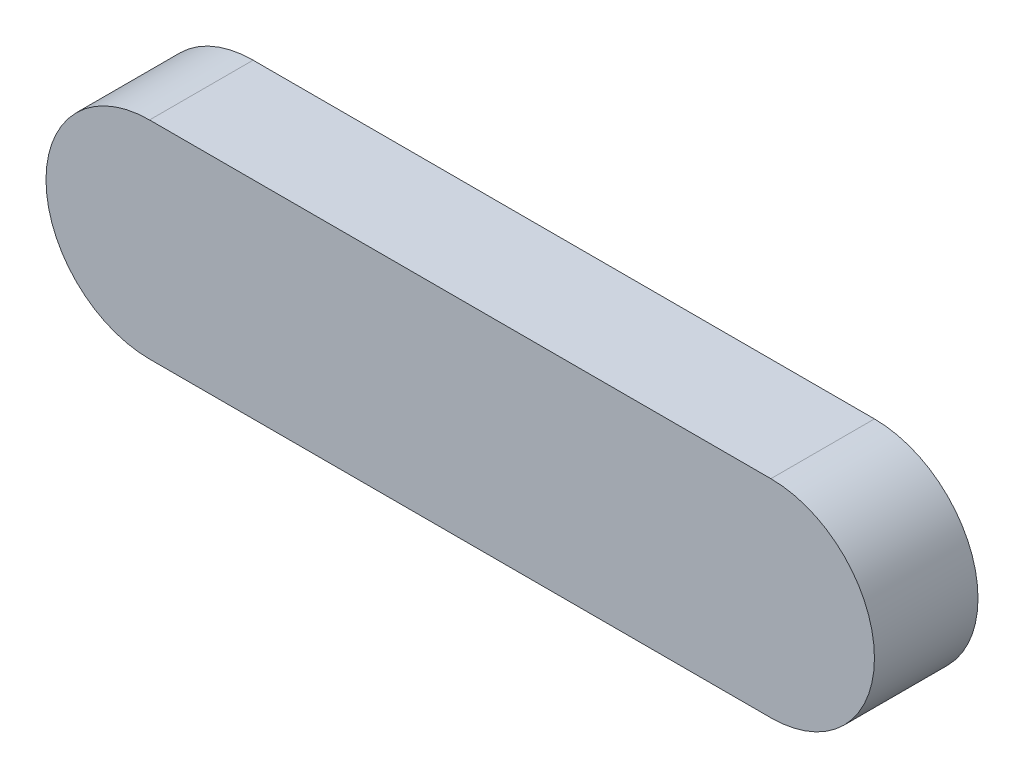
SolidWorks part; units mm, degrees
ref_plane "Front Plane" through (0, 0, 0) normal (0, 0, 1) x (1, 0, 0)
ref_plane "Top Plane" through (0, 0, 0) normal (0, 1, 0) x (1, 0, 0)
ref_plane "Right Plane" through (0, 0, 0) normal (1, 0, 0) x (0, 0, -1)
sketch "Sketch1" plane through (0, 0, 0) normal (0, 0, 1) x (1, 0, 0)
  line L0 (-15, 0) -> (15, 0) construction
  line L1 (-15, 5) -> (15, 5)
  line L2 (-15, -5) -> (15, -5)
  arc A0 (-15, 5) -> (-15, -5) centre (-15, 0) ccw
  arc A1 (15, -5) -> (15, 5) centre (15, 0) ccw
  point P2 (0, 0)
  dimension "D1" = 5
  dimension "D2" = 30
extrude "Boss-Extrude1" add sketch "Sketch1" along normal mid plane 5
